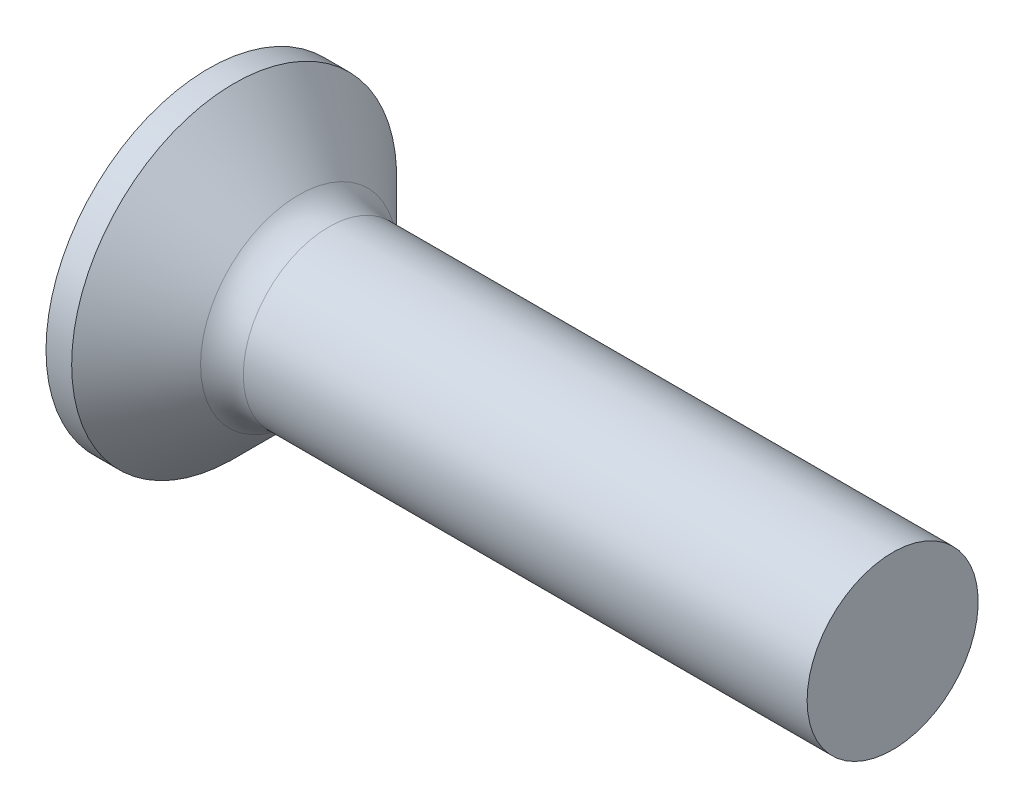
SolidWorks part; units mm, degrees
revolve "Base-Revolve" add sketch "BodySke"
sketch "BodySke" plane through (0, 0, 0) normal (0, 0, 1) x (1, 0, 0)
  line L0 (0, 0) -> (0, 1.9)
  line L1 (0, 1.9) -> (0.3, 1.9)
  line L2 (1.2, 1) -> (8, 1)
  line L3 (8, 1) -> (8, 0)
  line L4 (8, 0) -> (0, 0)
  line L5 (-6.35, 0) -> (82.55, 0) construction
  line L6 (1.2, -1) -> (8, -1) construction
  line L7 (0.3, -1.9) -> (1.2, -1) construction
  line L8 (0.3, 1.9) -> (1.2, 1)
  line L9 (0, -1.9) -> (0.3, -1.9) construction
  line L10 (1.6, 2.5875) -> (1.6, -6.9375) construction
  line L11 (0, 6.35) -> (0, -3.175) construction
  dimension "Diameter" = 2
  dimension "Length" = 8
  dimension "Head_ht" = 1.2
  dimension "Head_dia" = 3.8
  dimension "Head_ang" = 90
  dimension "D6" = 0.3
  dimension "Advance" = 0.4
  dimension "Thread_nom" = 8
cosmetic thread "ThreadCosmetic" [suppressed]
fillet "Fillet1" radius 0.5 1 edges at (1.2, 0, 1)
ref_plane "Plane1" through (0, 0, 0) normal (0, 0, 1) x (1, 0, 0)
ref_plane "Plane2" through (0, 0, 0) normal (0, 1, 0) x (1, 0, 0)
ref_plane "Plane3" through (0, 0, 0) normal (1, 0, 0) x (0, 0, -1)
sketch "Sketch3" plane through (0, 0, 0) normal (-1, 0, 0) x (0, 0, 1)
  line L0 (-0.24, 0.95) -> (0.24, 0.95)
  line L1 (0.24, 0.95) -> (0.24, -0.95)
  line L2 (0.24, -0.95) -> (-0.24, -0.95)
  line L3 (-0.24, -0.95) -> (-0.24, 0.95)
  dimension "Cross_dia" = 1.9
  dimension "Cross_width" = 0.48
  dimension "D1" = 0.95
  dimension "D2" = 0.24
ref_plane "Plane4" through (1.2, 0, 0) normal (-1, 0, 0) x (0, 0, 1)
sketch "Sketch4" plane through (1.2, 0, 0) normal (-1, 0, 0) x (0, 0, 1)
  line L0 (-0.24, 0.3517) -> (0.24, 0.3517)
  line L3 (0.24, 0.3517) -> (0.24, -0.3517)
  line L4 (0.24, -0.3517) -> (-0.24, -0.3517)
  line L5 (-0.24, -0.3517) -> (-0.24, 0.3517)
  dimension "D2" = 0.7034
  dimension "D1" = 0.48
  dimension "D4" = 0.3517
  dimension "D3" = 0.24
loft "Recess" cut profiles "Sketch3", "Sketch4"
pattern_circular "RecPat" count 2 every 90 about axis through (0, 0, 0) along (1, 0, 0) of "Recess"
sketch "RecCorSke" plane through (0, 0, 0) normal (0, 0, 1) x (1, 0, 0)
  line L0 (-3.175, 0) -> (15.875, 0) construction
  line L2 (0, 0) -> (0, 0.4394)
  line L3 (0, 0.4394) -> (1.2, 0.3555)
  line L4 (1.2, 0.3555) -> (1.3155, 0)
  line L5 (1.3155, 0) -> (0, 0)
  dimension "Diameter" = 0.711
  dimension "Depth" = 1.2
  dimension "Draft_angle" = 4
  dimension "Bottom_angle" = 18
revolve "RecessCore" cut sketch "RecCorSke" angle 360 about L0
sketch "ThdSchSke" plane through (0, 0, 0) normal (0, 0, 1) x (1, 0, 0)
  line L0 (1.6, -0.774) -> (1.4418, -1)
  line L1 (1.6, -0.774) -> (1.7582, -1)
  line L2 (1.7582, -1) -> (1.7582, -1.25)
  line L3 (-3.175, 0) -> (5.1513, 0) construction
  line L5 (1.7582, -1.25) -> (1.4418, -1.25)
  line L6 (1.4418, -1.25) -> (1.4418, -1)
  line L7 (0, 1.9) -> (0, -1.9) construction
  dimension "Diameter" = 2
  dimension "Thread_minor" = 1.548
  dimension "Start" = 1.6
revolve "ThreadSchematic" [suppressed] cut sketch "ThdSchSke" angle 360 about L3
pattern_linear "ThdSchPat" [suppressed]
equation "\"D1@Sketch3\" = \"Cross_dia@Sketch3\" / 2"
equation "\"D2@Sketch3\" = \"Cross_width@Sketch3\" / 2"
equation "\"Depth@RecCorSke\" = \"Cross_depth@Plane4\""
equation "\"D1@Sketch4\" = \"Cross_width@Sketch3\""
equation "\"D2@Sketch4\" = \"Cross_dia@Sketch3\" - 2.0 * \"Cross_depth@Plane4\" * tan(26.5  * 0.017453292)"
equation "\"D3@Sketch4\" = \"D1@Sketch4\" / 2"
equation "\"D4@Sketch4\" = \"D2@Sketch4\" / 2"
equation "\"Thread_length@ThreadCosmetic\" = ((sgn( (\"Length@BodySke\" - \"Advance@BodySke\" * 1.0 - \"Head_ht@BodySke\" ) - \"Thread_nom@BodySke\" )-1)*( (\"Length@BodySke\" - \"Advance@BodySke\" * 1.0 - \"Head_ht@BodySke\" ) - \"Thread_nom@BodySke\" ))/-2+ \"Thread_nom@BodySke\""
equation "\"Thread_minor@ThdSchSke\" = \"Thread_minor@ThreadCosmetic\""
equation "\"Diameter@ThdSchSke\" = \"Diameter@BodySke\""
equation "\"Overcut@ThdSchSke\" = \"Diameter@BodySke\" * 1.25"
equation "\"Start@ThdSchSke\" = 0.000001 + \"Length@BodySke\" - \"Thread_length@ThreadCosmetic\"  '---Countersunk---"
equation "\"Num_threads@ThdSchPat\" = int( \"Thread_length@ThreadCosmetic\" / \"Advance@BodySke\" + 0.999 )  + 1"
equation "\"Advance@ThdSchPat\" = \"Thread_length@ThreadCosmetic\" /  (\"Num_threads@ThdSchPat\" - 1) 'relax it"
